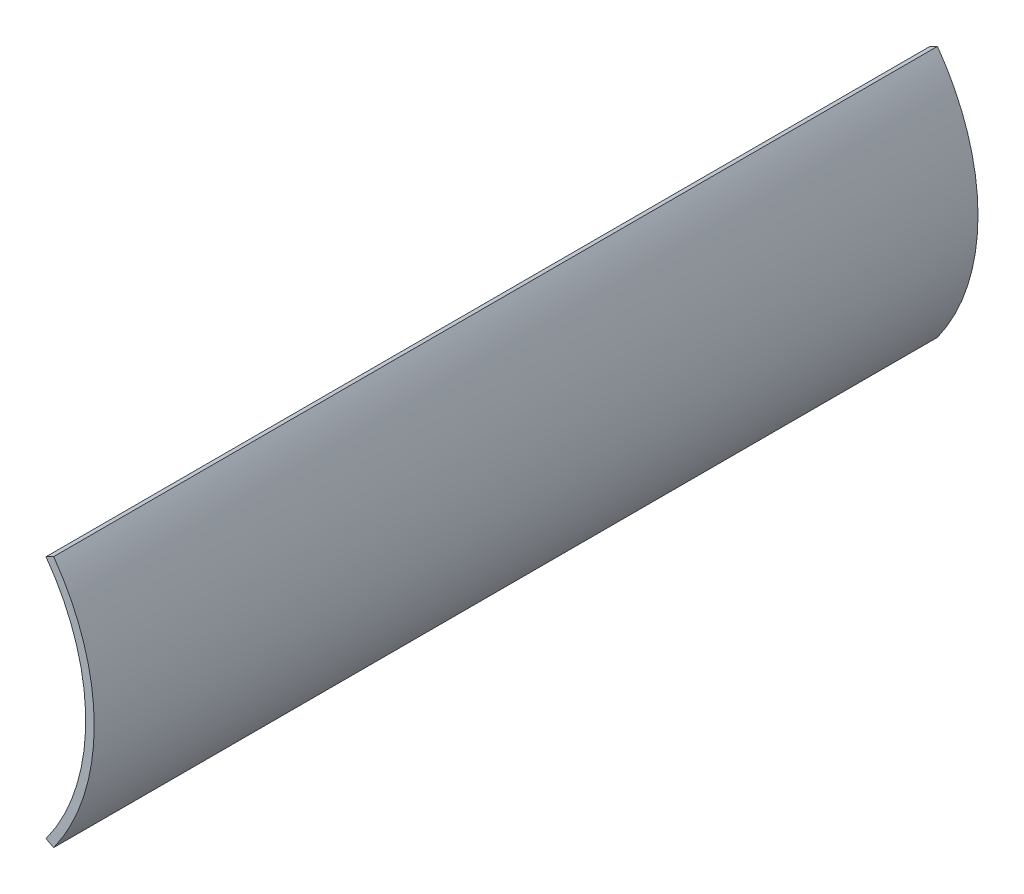
SolidWorks part; units mm, degrees
ref_plane "Спереди" through (0, 0, 0) normal (0, 0, 1) x (1, 0, 0)
ref_plane "Сверху" through (0, 0, 0) normal (0, 1, 0) x (1, 0, 0)
ref_plane "Справа" through (0, 0, 0) normal (1, 0, 0) x (0, 0, -1)
sketch "Эскиз1" plane through (0, 0, 0) normal (0, 0, 1) x (1, 0, 0)
  line L0 (-4.1594, 28.9649) -> (-2.3591, 29.8883)
  line L1 (-4.1594, -28.5033) -> (-2.3591, -29.4267)
  arc A0 (-4.1594, 28.9649) -> (-4.1594, -28.5033) centre (-43.6493, 0.2308) cw
  arc A1 (-2.3591, -29.4267) -> (-2.3591, 29.8883) centre (-43.6493, 0.2308) ccw
extrude "Бобышка-Вытянуть1" add sketch "Эскиз1" along normal blind 208
